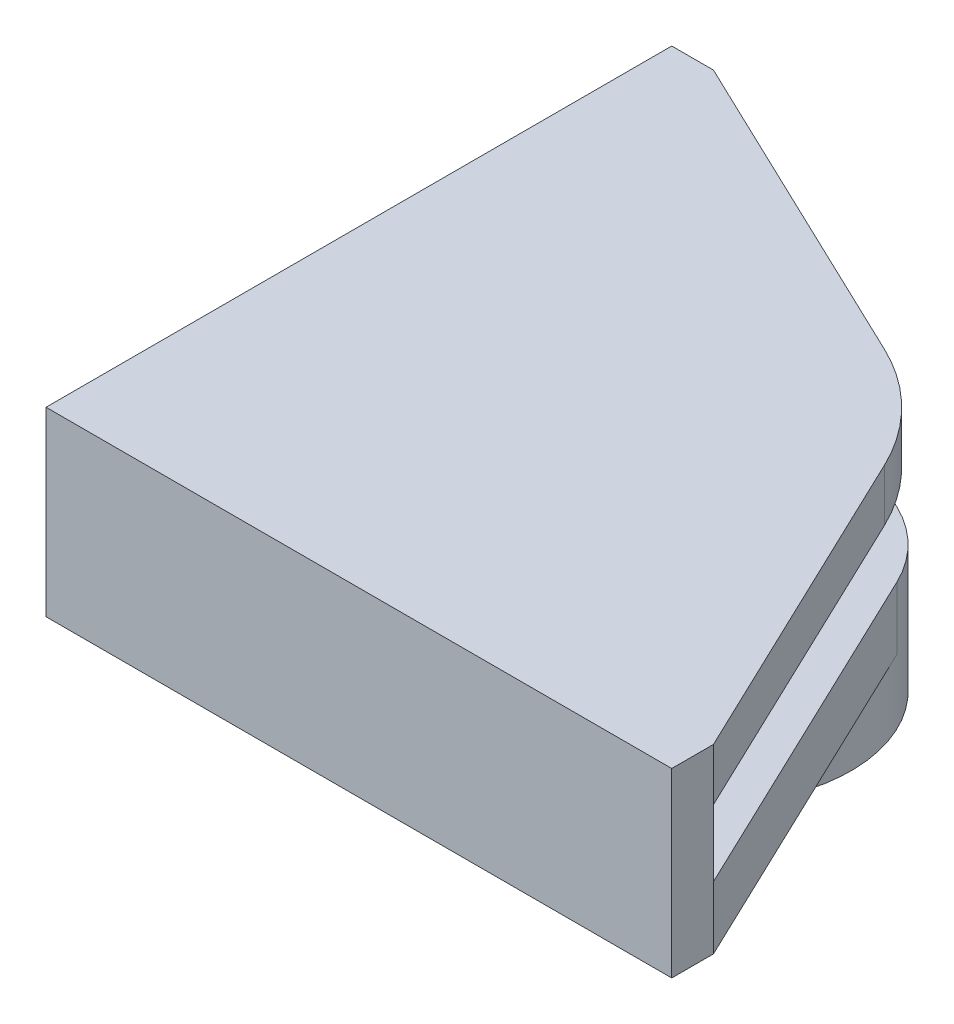
SolidWorks part; units mm, degrees
ref_plane "Front Plane" through (0, 0, 0) normal (0, 0, 1) x (1, 0, 0)
ref_plane "Top Plane" through (0, 0, 0) normal (0, 1, 0) x (1, 0, 0)
ref_plane "Right Plane" through (0, 0, 0) normal (1, 0, 0) x (0, 0, -1)
sketch "Sketch1" plane through (0, 0, 0) normal (0, 1, 0) x (1, 0, 0)
  line L0 (0, 0) -> (0, 28)
  line L1 (0, 28) -> (28, 0)
  line L2 (28, 0) -> (0, 0)
  circle A0 centre (14, 14) radius 5.1
  circle A1 centre (14, 14) radius 6.6
  dimension "D1" = 14
  dimension "D3" = 10.2
  dimension "D4" = 13.2
  dimension "D2" = 14
extrude "Boss-Extrude1" add sketch "Sketch1" along normal blind 3.1 contours L1 A1 A0 | L1 A1 A0
sketch "Sketch2" plane through (0, 3.1, 0) normal (0, 1, 0) x (1, 0, 0)
  line L0 (0, 0) -> (0, 28)
  line L1 (0, 28) -> (28, 0)
  line L2 (28, 0) -> (0, 0)
  line L3 (0, 28) -> (16.8443, 19.9557)
  line L4 (28, 0) -> (19.9557, 16.8443)
  line L5 (21.4946, 8.981) -> (23.8734, 4)
  line L6 (23.8734, 4) -> (18.6188, 4)
  line L7 (18.6188, 4) -> (21.4946, 8.981)
  line L8 (0, 0) -> (18.6669, 18.6669) construction
  line L9 (4, 23.8734) -> (4, 18.6188)
  line L10 (8.981, 21.4946) -> (4, 23.8734)
  line L11 (4, 18.6188) -> (8.981, 21.4946)
  circle A0 centre (14, 14) radius 6.6
  circle M11 centre (14, 14) radius 5.1
  circle M12 centre (14, 14) radius 6.6
  dimension "D1" = 13.2
  dimension "D2" = 2
  dimension "D3" = 4
  dimension "D4" = 9
  dimension "D5" = 60
extrude "Boss-Extrude2" add sketch "Sketch2" along normal blind 3 contours L11 L1 L3 L10 M12 | L0 L8 L1 L11 L9 L10 M12 | L8 L2 L1 L5 L6 L7 A0 | L1 L7 L5 L4 M12 | L8 L1 M11 M12 | L8 A0 L1 M11 M12 | L8 L1 M11 | L1 L8 M11 | L8 L1 M11 | L8 L1 M11 | L8 L1 M12 M11 | L8 A0 L1 M11
sketch "Sketch4" plane through (0, 6.1, 0) normal (0, 1, 0) x (1, 0, 0)
  line L0 (0, 28) -> (-2, 28)
  line L1 (-2, 28) -> (-2, -2)
  line L2 (-2, -2) -> (28, -2)
  line L3 (28, -2) -> (28, 0)
  line L4 (28, 0) -> (0, 0) construction
  line L5 (0, 0) -> (0, 28) construction
  line L10 (28, 0) -> (19.9557, 16.8443)
  line L11 (16.8443, 19.9557) -> (0, 28)
  line L12 (0, 28) -> (0, 0)
  line L13 (0, 0) -> (28, 0)
  line L16 (0, 28) -> (0, 0)
  line L17 (0, 0) -> (28, 0)
  arc A1 (19.9557, 16.8443) -> (16.8443, 19.9557) centre (14, 14) ccw
  dimension "D1" = 2
  dimension "D2" = 2
  dimension "D3" = 0
extrude "Boss-Extrude4" add sketch "Sketch4" against normal blind 3 and the other way blind 3.2
sketch "Sketch5" plane through (0, 9.3, 0) normal (0, 1, 0) x (1, 0, 0)
  line L0 (-2, 28) -> (0, 28)
  line L1 (0, 28) -> (15.6957, 20.5042)
  line L2 (20.5042, 15.6957) -> (28, 0)
  line L3 (28, 0) -> (28, -2)
  line L4 (28, -2) -> (-2, -2)
  line L5 (-2, -2) -> (-2, 28)
  line L6 (28, 0) -> (19.9557, 16.8443) construction
  line L7 (0, 28) -> (16.8443, 19.9557) construction
  arc A0 (15.6957, 20.5042) -> (20.5042, 15.6957) centre (11.3, 11.3) cw
  dimension "D1" = 10.2
extrude "Boss-Extrude5" add sketch "Sketch5" along normal blind 2.5
